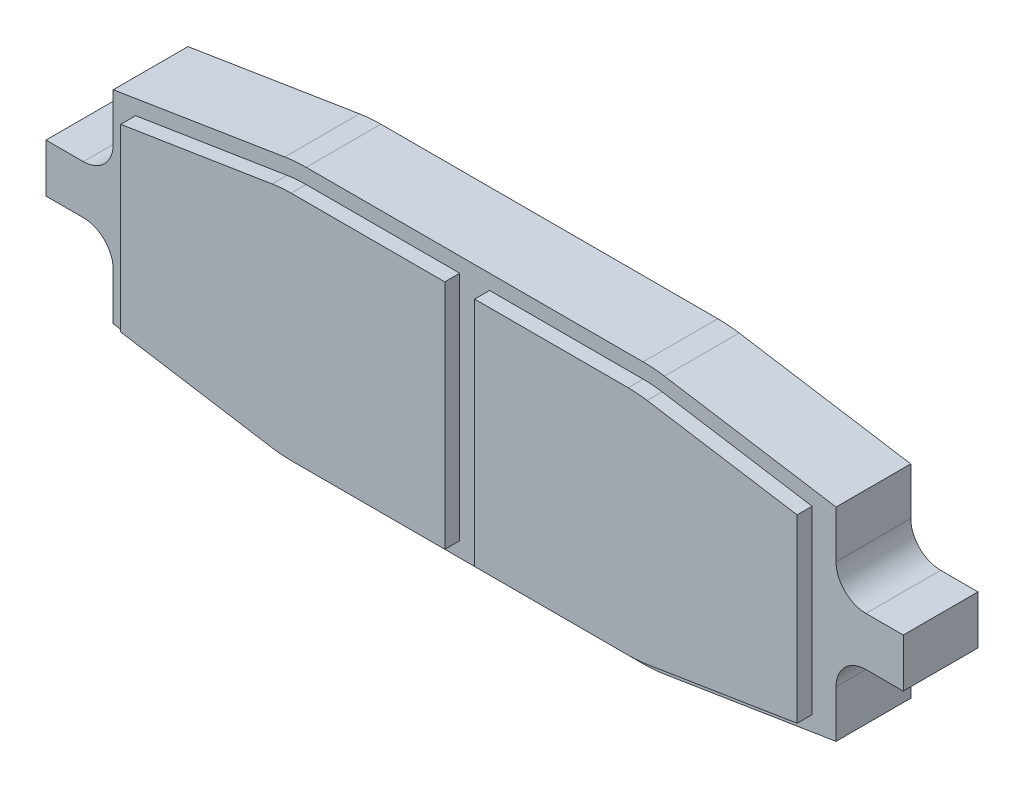
SolidWorks part; units mm, degrees
ref_plane "Front Plane" through (0, 0, 0) normal (0, 0, 1) x (1, 0, 0)
ref_plane "Top Plane" through (0, 0, 0) normal (0, 1, 0) x (1, 0, 0)
ref_plane "Right Plane" through (0, 0, 0) normal (1, 0, 0) x (0, 0, -1)
sketch "Sketch1" plane through (0, 0, 0) normal (0, 0, 1) x (1, 0, 0)
  line L0 (0, 39.6686) -> (0, -39.6686) construction
  line L1 (-50.3702, -14.1004) -> (-50.3702, -7.1004) construction
  line L2 (-50.3702, -9.1004) -> (-50.3702, -17.1004) construction
  line L3 (-52.3702, -7.1004) -> (-57.3702, -7.1004) construction
  line L4 (-52.3702, 3.3996) -> (-57.3702, 3.3996) construction
  line L5 (-59.3702, -5.1004) -> (-59.3702, 1.3996) construction
  line L6 (-50.3702, 5.3996) -> (-50.3702, 11.7334) construction
  line L7 (-50.3702, 17.1114) -> (54.6448, 17.1114) construction
  line L8 (-22.5495, 17.6496) -> (22.5495, 17.6496) construction
  line L9 (-48.6873, 13.7081) -> (-25.7209, 17.3966) construction
  line L10 (48.6873, 13.7081) -> (25.7209, 17.3966) construction
  line L11 (50.3702, 5.3996) -> (50.3702, 11.7334) construction
  line L12 (59.3702, -5.1004) -> (59.3702, 1.3996) construction
  line L13 (52.3702, 3.3996) -> (57.3702, 3.3996) construction
  line L15 (52.3702, -7.1004) -> (57.3702, -7.1004) construction
  line L16 (50.3702, -9.1004) -> (50.3702, -17.1386) construction
  line L17 (-50.3702, 3.3996) -> (-50.3702, 34.3996) construction
  line L18 (-59.3702, -1.8504) -> (59.3702, -1.8504) construction
  line L19 (50.3702, -17.1386) -> (25.7209, -21.0973) construction
  line L20 (-50.3702, -17.1004) -> (-25.7209, -21.0973) construction
  line L21 (-22.5495, -21.3504) -> (22.5495, -21.3504) construction
  line L22 (-48.3702, -9.1004) -> (-48.3702, -15.3986)
  line L23 (-48.3702, -15.3986) -> (-25.4023, -19.1229)
  line L24 (-22.5495, -19.3504) -> (22.5495, -19.3504)
  line L25 (48.3702, -15.4342) -> (25.4037, -19.1226)
  line L26 (48.3702, -9.1004) -> (48.3702, -15.4342)
  line L27 (52.3702, -5.1004) -> (57.3702, -5.1004)
  line L28 (57.3702, -5.1004) -> (57.3702, 1.3996)
  line L29 (52.3702, 1.3996) -> (57.3702, 1.3996)
  line L30 (48.3702, 5.3996) -> (48.3702, 11.7334)
  line L31 (48.3702, 11.7334) -> (25.4037, 15.4219)
  line L32 (-22.5495, 15.6496) -> (22.5495, 15.6496)
  line L33 (-48.3702, 11.7334) -> (-25.4037, 15.4219)
  line L34 (-48.3702, 5.3996) -> (-48.3702, 11.7334)
  line L35 (-52.3702, 1.3996) -> (-57.3702, 1.3996)
  line L36 (-57.3702, -5.1004) -> (-57.3702, 1.3996)
  line L37 (-52.3702, -5.1004) -> (-57.3702, -5.1004)
  circle A0 centre (0, -12.6004) radius 32.8 construction
  circle A1 centre (-71.6851, -12.6004) radius 5.115 construction
  arc A2 (25.7209, 17.3966) -> (22.5495, 17.6496) centre (22.5495, -2.3504) ccw construction
  arc A3 (-25.7209, 17.3966) -> (-22.5495, 17.6496) centre (-22.5495, -2.3504) cw construction
  arc A4 (59.3702, 1.3996) -> (57.3702, 3.3996) centre (57.3702, 1.3996) ccw construction
  arc A5 (59.3702, -5.1004) -> (57.3702, -7.1004) centre (57.3702, -5.1004) cw construction
  arc A6 (50.3702, -9.1004) -> (52.3702, -7.1004) centre (52.3702, -9.1004) cw construction
  arc A7 (50.3702, 5.3996) -> (52.3702, 3.3996) centre (52.3702, 5.3996) ccw construction
  arc A8 (48.6873, 13.7081) -> (50.3702, 11.7334) centre (48.3702, 11.7334) cw construction
  arc A9 (-50.3702, 11.7334) -> (-48.6873, 13.7081) centre (-48.3702, 11.7334) cw construction
  arc A10 (-52.3702, -7.1004) -> (-50.3702, -9.1004) centre (-52.3702, -9.1004) cw construction
  arc A11 (-50.3702, 5.3996) -> (-52.3702, 3.3996) centre (-52.3702, 5.3996) cw construction
  arc A12 (-57.3702, 3.3996) -> (-59.3702, 1.3996) centre (-57.3702, 1.3996) ccw construction
  arc A13 (-57.3702, -7.1004) -> (-59.3702, -5.1004) centre (-57.3702, -5.1004) cw construction
  arc A14 (25.7209, -21.0973) -> (22.5495, -21.3504) centre (22.5495, -1.3504) cw construction
  arc A15 (-25.7209, -21.0973) -> (-22.5495, -21.3504) centre (-22.5495, -1.3504) ccw construction
  arc A16 (-25.4023, -19.1229) -> (-22.5495, -19.3504) centre (-22.5495, -1.3504) ccw
  arc A17 (25.4037, -19.1226) -> (22.5495, -19.3504) centre (22.5495, -1.3504) cw
  arc A18 (48.3702, -9.1004) -> (52.3702, -5.1004) centre (52.3702, -9.1004) cw
  arc A21 (48.3702, 5.3996) -> (52.3702, 1.3996) centre (52.3702, 5.3996) ccw
  arc A23 (25.4037, 15.4219) -> (22.5495, 15.6496) centre (22.5495, -2.3504) ccw
  arc A24 (-25.4037, 15.4219) -> (-22.5495, 15.6496) centre (-22.5495, -2.3504) cw
  arc A26 (-48.3702, 5.3996) -> (-52.3702, 1.3996) centre (-52.3702, 5.3996) cw
  arc A29 (-52.3702, -5.1004) -> (-48.3702, -9.1004) centre (-52.3702, -9.1004) cw
  arc A30 (-57.3702, -5.1004) -> (-57.3702, -5.1004) centre (-57.3702, -5.1004) cw construction
  arc A31 (-57.3702, 1.3996) -> (-57.3702, 1.3996) centre (-57.3702, 1.3996) ccw construction
  arc A32 (-48.3702, 11.7334) -> (-48.3702, 11.7334) centre (-48.3702, 11.7334) cw construction
  arc A33 (48.3702, 11.7334) -> (48.3702, 11.7334) centre (48.3702, 11.7334) cw construction
  arc A34 (57.3702, 1.3996) -> (57.3702, 1.3996) centre (57.3702, 1.3996) ccw construction
  arc A35 (57.3702, -5.1004) -> (57.3702, -5.1004) centre (57.3702, -5.1004) cw construction
  point P19 (0, 17.6496)
  point P51 (0, 0)
  dimension "D1" = 65.6
  dimension "D2" = 20
  dimension "D3" = 8
  dimension "D4" = 2
  dimension "D5" = 6.5
  dimension "D6" = 35
extrude "Boss-Extrude1" add sketch "Sketch1" along normal blind 10 contours L37 A29 L22 L23 A16 L24 A17 L25 L26 A18 L27 L28 L29 A21 L30 L31 A23 L32 A24 L33 L34 A26 L35 L36
sketch "Sketch2" plane through (0, 0, 10) normal (0, 0, 1) x (1, 0, 0)
  line L0 (0, 15.6496) -> (0, -19.3504) construction
  line L1 (-2, 13.6496) -> (-2, -17.3504)
  line L2 (2, 13.6496) -> (2, -17.3504)
  line L3 (-45.3702, 10.2225) -> (-45.3702, -13.8589)
  line L4 (45.1654, 10.2225) -> (45.1654, -13.9345)
  line L6 (2, -19.3504) -> (22.5495, -19.3504)
  line L7 (-25.0881, 13.4469) -> (-45.3702, 10.2225)
  line L9 (-45.3702, -13.8589) -> (-25.0838, -17.1484)
  line L10 (-22.5495, -17.3504) -> (-2, -17.3504)
  line L11 (-4, 13.6496) -> (-4, -17.3504) construction
  line L12 (-2, 13.6496) -> (-22.5495, 13.6496)
  line L13 (22.5495, 13.6496) -> (2, 13.6496)
  line L14 (4, 13.6496) -> (4, -17.3504) construction
  line L15 (2, -17.3504) -> (22.5495, -17.3504)
  line L16 (-57.3702, -5.1004) -> (-52.3702, -5.1004)
  line L17 (-48.3702, -9.1004) -> (-48.3702, -15.3986)
  line L18 (-48.3702, -15.3986) -> (-25.4023, -19.1229)
  line L19 (-22.5495, -19.3504) -> (22.5495, -19.3504)
  line L20 (25.4037, -19.1226) -> (48.3702, -15.4342)
  line L21 (48.3702, -15.4342) -> (48.3702, -9.1004)
  line L22 (52.3702, -5.1004) -> (57.3702, -5.1004)
  line L23 (57.3702, -5.1004) -> (57.3702, 1.3996)
  line L24 (57.3702, 1.3996) -> (52.3702, 1.3996)
  line L25 (48.3702, 5.3996) -> (48.3702, 11.7334)
  line L26 (48.3702, 11.7334) -> (25.4037, 15.4219)
  line L27 (22.5495, 15.6496) -> (-22.5495, 15.6496)
  line L28 (-25.4037, 15.4219) -> (-48.3702, 11.7334)
  line L29 (-48.3702, 11.7334) -> (-48.3702, 5.3996)
  line L30 (-52.3702, 1.3996) -> (-57.3702, 1.3996)
  line L31 (-57.3702, 1.3996) -> (-57.3702, -5.1004)
  line L32 (-57.3702, -5.1004) -> (-52.3702, -5.1004) construction
  line L33 (-48.3702, -9.1004) -> (-48.3702, -15.3986) construction
  line L34 (-45.3702, -15.885) -> (-25.4023, -19.1229)
  line L35 (-22.5495, -19.3504) -> (-2, -19.3504)
  line L37 (48.3702, -15.4342) -> (48.3702, -9.1004) construction
  line L38 (52.3702, -5.1004) -> (57.3702, -5.1004) construction
  line L39 (57.3702, -5.1004) -> (57.3702, 1.3996) construction
  line L40 (57.3702, 1.3996) -> (52.3702, 1.3996) construction
  line L41 (48.3702, 5.3996) -> (48.3702, 11.7334) construction
  line L42 (45.1654, 12.2481) -> (25.4037, 15.4219)
  line L43 (22.5495, 15.6496) -> (2, 15.6496)
  line L45 (-48.3702, 11.7334) -> (-48.3702, 5.3996) construction
  line L46 (-52.3702, 1.3996) -> (-57.3702, 1.3996) construction
  line L47 (-57.3702, 1.3996) -> (-57.3702, -5.1004) construction
  line L48 (25.0871, -17.1479) -> (45.1654, -13.9345)
  line L49 (43.1654, 10.5437) -> (43.1654, -14.2546) construction
  line L50 (45.1654, 10.2225) -> (25.0866, 13.4472)
  line L51 (-25.0881, 13.4469) -> (-43.3702, 10.5404) construction
  line L52 (-43.3702, -14.1832) -> (-25.0838, -17.1484) construction
  line L53 (-45.3702, 12.2476) -> (-45.3702, -15.885) construction
  line L54 (43.1654, 10.5437) -> (25.0866, 13.4472) construction
  line L55 (-43.3702, 10.5404) -> (-43.3702, -14.1832) construction
  line L56 (-25.4037, 15.4219) -> (-45.3702, 12.2476) construction
  line L57 (-2, 15.6496) -> (-22.5495, 15.6496) construction
  line L58 (25.0871, -17.1479) -> (43.1654, -14.2546) construction
  line L59 (25.4037, -19.1226) -> (45.1654, -15.9599) construction
  line L60 (45.1654, 12.2481) -> (45.1654, -15.9599) construction
  line L61 (-4, 13.6496) -> (-22.5495, 13.6496) construction
  line L62 (-22.5495, -17.3504) -> (-4, -17.3504) construction
  line L63 (4, -17.3504) -> (22.5495, -17.3504) construction
  line L64 (22.5495, 13.6496) -> (4, 13.6496) construction
  line L65 (-2, 15.6496) -> (-2, -19.3504) construction
  line L66 (2, 15.6496) -> (2, -19.3504) construction
  arc A0 (-25.0838, -17.1484) -> (-22.5495, -17.3504) centre (-22.5495, -1.3504) ccw
  arc A1 (-22.5495, 13.6496) -> (-25.0881, 13.4469) centre (-22.5495, -2.3504) ccw
  arc A2 (22.5495, -17.3504) -> (25.0871, -17.1479) centre (22.5495, -1.3504) ccw
  arc A3 (25.0866, 13.4472) -> (22.5495, 13.6496) centre (22.5495, -2.3504) ccw
  arc A8 (-48.3702, -9.1004) -> (-52.3702, -5.1004) centre (-52.3702, -9.1004) ccw
  arc A9 (-25.4023, -19.1229) -> (-22.5495, -19.3504) centre (-22.5495, -1.3504) ccw
  arc A10 (22.5495, -19.3504) -> (25.4037, -19.1226) centre (22.5495, -1.3504) ccw
  arc A11 (52.3702, -5.1004) -> (48.3702, -9.1004) centre (52.3702, -9.1004) ccw
  arc A12 (48.3702, 5.3996) -> (52.3702, 1.3996) centre (52.3702, 5.3996) ccw
  arc A13 (25.4037, 15.4219) -> (22.5495, 15.6496) centre (22.5495, -2.3504) ccw
  arc A14 (-22.5495, 15.6496) -> (-25.4037, 15.4219) centre (-22.5495, -2.3504) ccw
  arc A15 (-52.3702, 1.3996) -> (-48.3702, 5.3996) centre (-52.3702, 5.3996) ccw
  arc A16 (-48.3702, -9.1004) -> (-52.3702, -5.1004) centre (-52.3702, -9.1004) ccw construction
  arc A17 (-25.4023, -19.1229) -> (-22.5495, -19.3504) centre (-22.5495, -1.3504) ccw
  arc A18 (22.5495, -19.3504) -> (25.4037, -19.1226) centre (22.5495, -1.3504) ccw
  arc A19 (52.3702, -5.1004) -> (48.3702, -9.1004) centre (52.3702, -9.1004) ccw construction
  arc A20 (48.3702, 5.3996) -> (52.3702, 1.3996) centre (52.3702, 5.3996) ccw construction
  arc A21 (25.4037, 15.4219) -> (22.5495, 15.6496) centre (22.5495, -2.3504) ccw
  arc A23 (-52.3702, 1.3996) -> (-48.3702, 5.3996) centre (-52.3702, 5.3996) ccw construction
  arc A24 (-22.5495, 15.6496) -> (-25.4037, 15.4219) centre (-22.5495, -2.3504) ccw construction
  dimension "D4" = 2
  dimension "3" = 3
  dimension "D1" = 0
  dimension "D2" = 2
  dimension "D3" = 2
extrude "Boss-Extrude2" add sketch "Sketch2" along normal blind 2 contours L50 A3 L13 L14 L15 A2 L48 L4 | L12 A1 L7 L3 L9 A0 L10 L11
